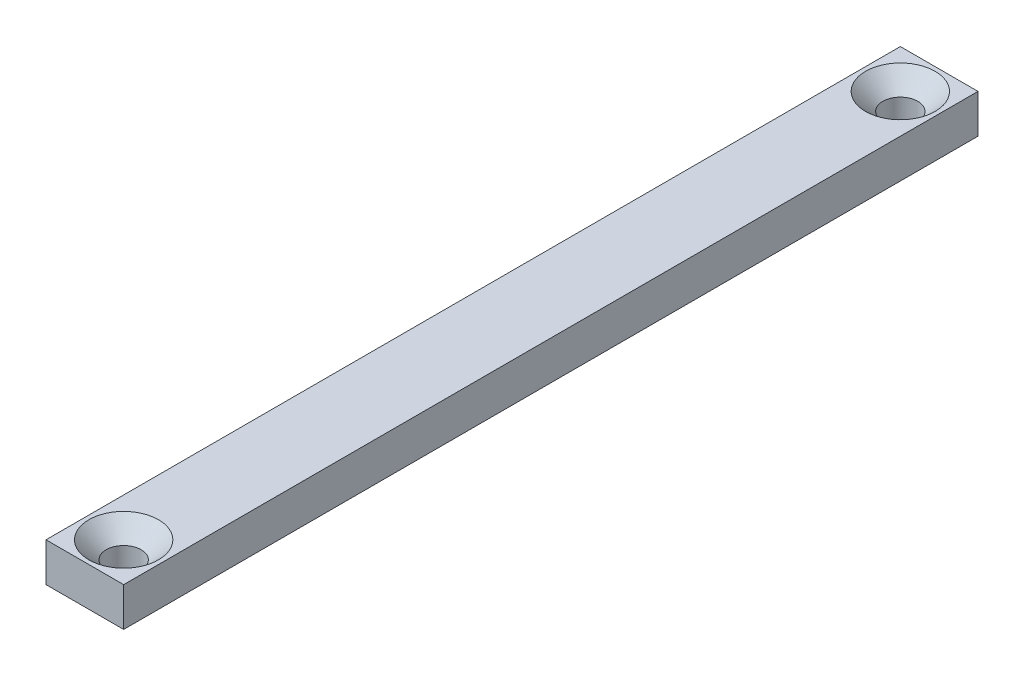
SolidWorks part; units mm, degrees
ref_plane "Front Plane" through (0, 0, 0) normal (0, 0, 1) x (1, 0, 0)
ref_plane "Top Plane" through (0, 0, 0) normal (0, 1, 0) x (1, 0, 0)
ref_plane "Right Plane" through (0, 0, 0) normal (1, 0, 0) x (0, 0, -1)
sketch "Sketch1" plane through (0, 0, 0) normal (0, 1, 0) x (1, 0, 0)
  line L1 (-5, -55) -> (5, -55)
  line L2 (-5, -55) -> (-5, 55)
  line L3 (-5, 55) -> (5, 55)
  line L4 (5, -55) -> (5, 55)
  line L5 (-5, -55) -> (5, 55) construction
  line L6 (-5, 55) -> (5, -55) construction
  point P0 (0, 0)
  dimension "D1" = 110
  dimension "D2" = 10
extrude "Boss-Extrude1" add sketch "Sketch1" along normal blind 5
hole_wizard "CSK for M4 SFHCS1" positions "Sketch2" profile "Sketch4" countersink size "M4" standard "ANSI Metric" end condition through all
sketch "Sketch2" plane through (0, 5, 0) normal (0, 1, 0) x (1, 0, 0)
  line L0 (0, -50) -> (0, 50)
  point P0 (0, -50)
  point P1 (0, 50)
  point P4 (0, 0)
  dimension "D1" = 100
sketch "Sketch4" plane through (0, 5, 50) normal (1, 0, 0) x (0, 0, 1)
  line L0 (0, 0) -> (0, 5)
  line L1 (0, 5) -> (2.25, 5)
  line L2 (2.25, 5) -> (2.25, 2.23)
  line L3 (2.25, 2.23) -> (4.48, 0)
  line L5 (4.48, 0) -> (0, 0)
  line L6 (-2.25, 2.23) -> (-4.48, 0) construction
  line L11 (0, -6.35) -> (0, 107.95) construction
  dimension "Thru Hole Dia." = 4.5
  dimension "Thru Hole Depth" = 5
  dimension "Near C'Sink Dia." = 8.96
  dimension "Near C'Sink Angle" = 90
